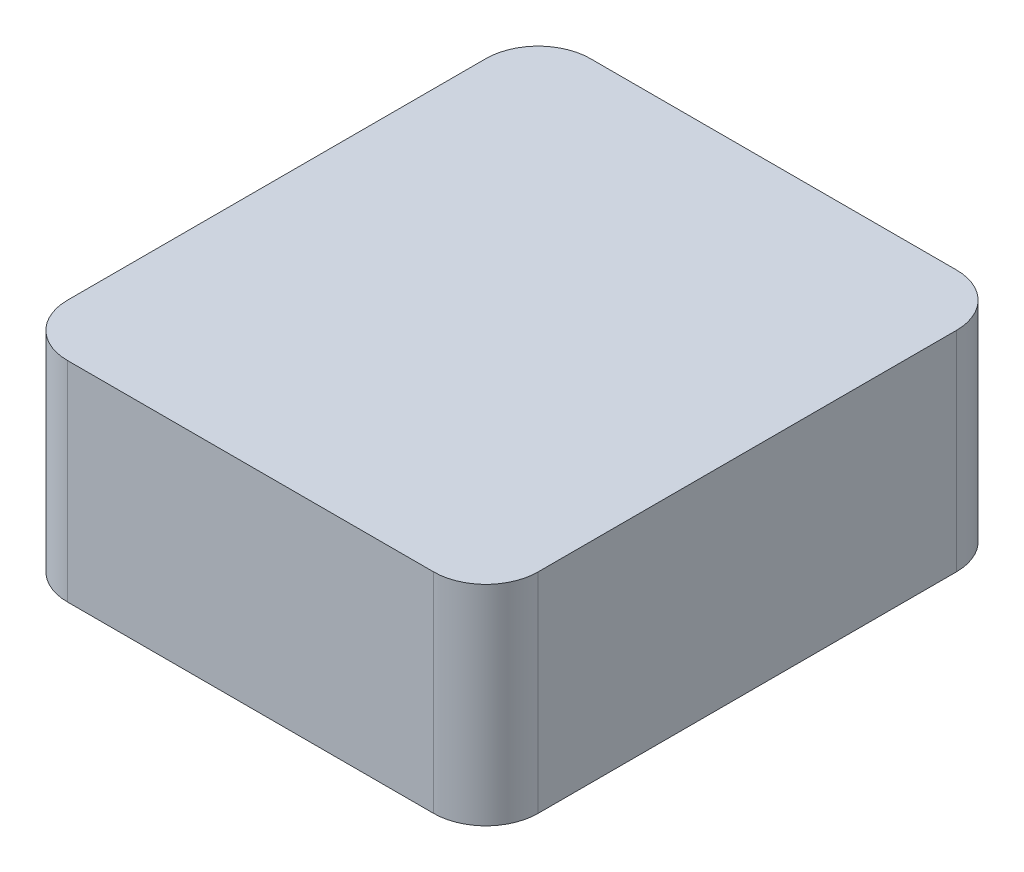
SolidWorks part; units mm, degrees
ref_plane "Front Plane" through (0, 0, 0) normal (0, 0, 1) x (1, 0, 0)
ref_plane "Top Plane" through (0, 0, 0) normal (0, 1, 0) x (1, 0, 0)
ref_plane "Right Plane" through (0, 0, 0) normal (1, 0, 0) x (0, 0, -1)
sketch "Sketch1" plane through (0, 0, 0) normal (0, 1, 0) x (1, 0, 0)
  line L1 (-8.0863, 17.3117) -> (81.9137, 17.3117)
  line L2 (-8.0863, 17.3117) -> (-8.0863, -82.6883)
  line L3 (-8.0863, -82.6883) -> (81.9137, -82.6883)
  line L4 (81.9137, 17.3117) -> (81.9137, -82.6883)
  dimension "D1" = 90
  dimension "D2" = 100
extrude "Boss-Extrude1" add sketch "Sketch1" along normal blind 40
shell "Shell1" thickness 3
fillet "Fillet1" radius 10 1 edges at (81.9137, 20, 82.6883)
fillet "Fillet2" radius 10 1 edges at (-8.0863, 20, 82.6883)
fillet "Fillet3" radius 10 1 edges at (81.9137, 20, -17.3117)
fillet "Fillet4" radius 10 1 edges at (-8.0863, 20, -17.3117)
